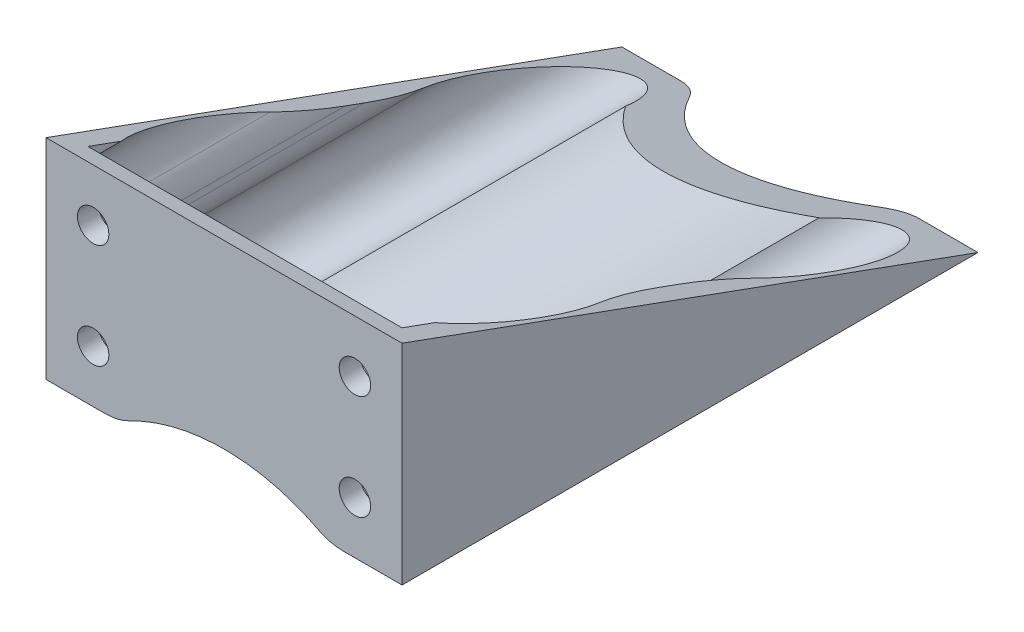
SolidWorks part; units mm, degrees
ref_plane "Alzado" through (0, 0, 0) normal (0, 0, 1) x (1, 0, 0)
ref_plane "Planta" through (0, 0, 0) normal (0, 1, 0) x (1, 0, 0)
ref_plane "Vista lateral" through (0, 0, 0) normal (1, 0, 0) x (0, 0, -1)
sketch "Croquis4" plane through (0, 0, 0) normal (1, 0, 0) x (0, 0, -1)
  line L0 (0, 0) -> (55, 0)
  line L1 (55, 0) -> (0, 20)
  line L2 (0, 20) -> (0, 0)
  dimension "D1" = 20
  dimension "D2" = 55
extrude "Saliente-Extruir3" add sketch "Croquis4" along normal blind 34
sketch "Croquis5" plane through (0, 0, 0) normal (0, 0, 1) x (1, 0, 0)
  line L0 (0, 0) -> (34, 20) construction
  line L2 (29.5, 5) -> (4.5, 5)
  line L3 (29.5, 5) -> (29.5, 15)
  line L4 (29.5, 15) -> (4.5, 15)
  line L5 (4.5, 5) -> (4.5, 15)
  line L6 (29.5, 5) -> (4.5, 15) construction
  line L7 (29.5, 15) -> (4.5, 5) construction
  circle A0 centre (4.5, 15) radius 1.5
  circle A1 centre (29.5, 15) radius 1.5
  circle A2 centre (29.5, 5) radius 1.5
  circle A3 centre (4.5, 5) radius 1.5
  point P4 (17, 10)
  dimension "D3" = 2
  dimension "D1" = 25
  dimension "D2" = 10
  dimension "D4" = 2
sketch "Croquis6" plane through (0, 0, 0) normal (0, 0, 1) x (1, 0, 0)
  line L0 (17, 0) -> (17, -17) construction
  line L1 (34, 0) -> (0, 0) construction
  circle A0 centre (17, -17) radius 19.75
  dimension "D1" = 39.5
  dimension "D2" = 17
extrude "Cortar-Extruir2" cut sketch "Croquis6" against normal through all
shell "Vaciado3" thickness 2
extrude "Cortar-Extruir3" cut sketch "Croquis5" against normal blind 10 contours A0 | A1 | A2 | A3
fillet "Redondeo1" radius 5 2 edges at (27.053, 0, -27.5) (6.947, 0, -27.5)
fillet "Redondeo3" radius 5 2 edges at (6.414, 2, -25.75) (27.586, 2, -25.75)
ref_plane "Plano1" through (0, 0, -30) normal (0, 0, 1) x (1, 0, 0)
sketch "Croquis10" plane through (0, 0, -2) normal (0, 0, -1) x (-1, 0, 0)
  circle A0 centre (-29.5, 15) radius 4
  circle A1 centre (-4.5, 15) radius 4
  circle A2 centre (-4.5, 5) radius 4
  circle A3 centre (-29.5, 5) radius 4
  dimension "D1" = 8
  dimension "D2" = 2
  dimension "D3" = 2
extrude "Cortar-Extruir7" cut sketch "Croquis10" along normal through all
fillet "Redondeo4" radius 4 4 edges at (2, 8.1225, -17.3316) (2, 11.8775, -12.1684) (32, 8.1225, -17.3316) (32, 11.8775, -12.1684)
